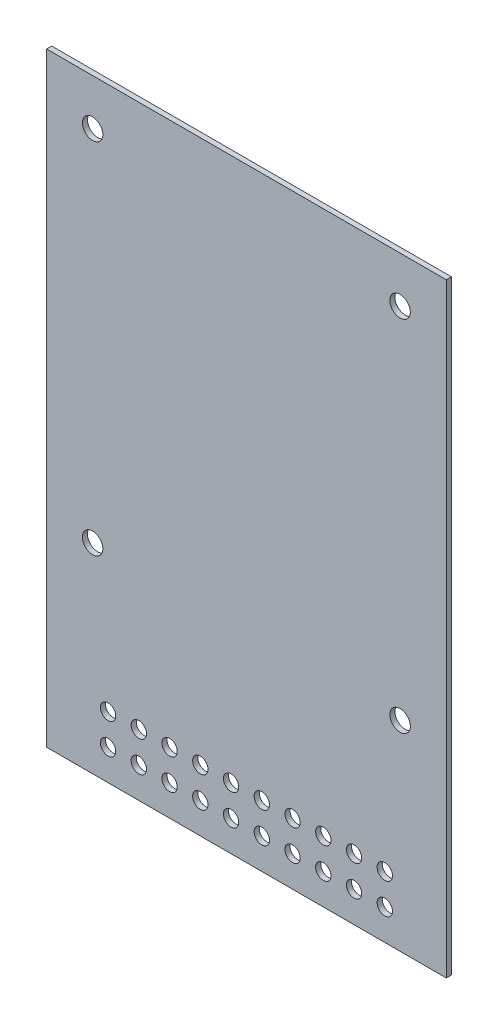
SolidWorks part; units mm, degrees
ref_plane "Front Plane" through (0, 0, 0) normal (0, 0, 1) x (1, 0, 0)
ref_plane "Top Plane" through (0, 0, 0) normal (0, 1, 0) x (1, 0, 0)
ref_plane "Right Plane" through (0, 0, 0) normal (1, 0, 0) x (0, 0, -1)
sketch "Sketch1" plane through (0, 0, 0) normal (0, 0, 1) x (1, 0, 0)
  line L1 (0, 0) -> (78, 0)
  line L2 (0, 0) -> (0, 118)
  line L3 (0, 118) -> (78, 118)
  line L4 (78, 0) -> (78, 118)
  dimension "D1" = 78
  dimension "D2" = 118
extrude "Boss-Extrude1" add sketch "Sketch1" along normal blind 1
sketch "Sketch2" plane through (0, 0, 0) normal (0, 0, -1) x (-1, 0, 0)
  line L0 (-78, 0) -> (-78, 118) construction
  line L1 (0, 0) -> (-78, 0) construction
  circle A0 centre (-8.9804, 39.0168) radius 2
  circle A1 centre (-68.9804, 39.0168) radius 2
  circle A2 centre (-68.9804, 109.0168) radius 2
  circle A3 centre (-8.9804, 109.0168) radius 2
  circle A4 centre (-66, 12) radius 1.5
  circle A5 centre (-60, 12) radius 1.5
  circle A6 centre (-54, 12) radius 1.5
  circle A7 centre (-48, 12) radius 1.5
  circle A8 centre (-42, 12) radius 1.5
  circle A9 centre (-36, 12) radius 1.5
  circle A10 centre (-30, 12) radius 1.5
  circle A11 centre (-24, 12) radius 1.5
  circle A12 centre (-18, 12) radius 1.5
  circle A13 centre (-12, 12) radius 1.5
  circle A14 centre (-60, 6) radius 1.5
  circle A15 centre (-54, 6) radius 1.5
  circle A16 centre (-48, 6) radius 1.5
  circle A17 centre (-42, 6) radius 1.5
  circle A18 centre (-36, 6) radius 1.5
  circle A19 centre (-30, 6) radius 1.5
  circle A20 centre (-24, 6) radius 1.5
  circle A21 centre (-18, 6) radius 1.5
  circle A22 centre (-12, 6) radius 1.5
  circle A23 centre (-66, 6) radius 1.5
  dimension "D1" = 4
  dimension "D4" = 10
  dimension "D8" = 3
  dimension "D6" = 12
  dimension "D7" = 12
  dimension "D2" = 2
  dimension "D3" = 2
  dimension "D5" = 2
extrude "Cut-Extrude1" cut sketch "Sketch2" against normal through all
